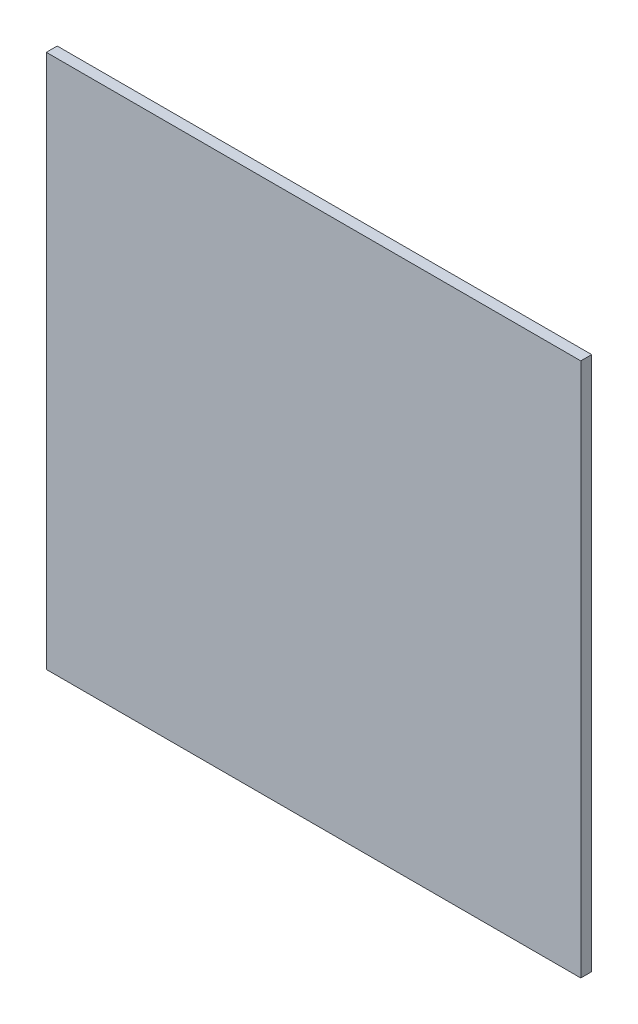
SolidWorks part; units mm, degrees
ref_plane "前视基准面" through (0, 0, 0) normal (0, 0, 1) x (1, 0, 0)
ref_plane "上视基准面" through (0, 0, 0) normal (0, 1, 0) x (1, 0, 0)
ref_plane "右视基准面" through (0, 0, 0) normal (1, 0, 0) x (0, 0, -1)
sketch "草图1" plane through (0, 0, 0) normal (0, 0, 1) x (1, 0, 0)
  line L1 (-2.45, -2.45) -> (2.45, -2.45)
  line L2 (-2.45, -2.45) -> (-2.45, 2.45)
  line L3 (-2.45, 2.45) -> (2.45, 2.45)
  line L4 (2.45, -2.45) -> (2.45, 2.45)
  line L5 (-2.45, -2.45) -> (2.45, 2.45) construction
  line L6 (-2.45, 2.45) -> (2.45, -2.45) construction
  point P0 (0, 0)
  dimension "D1" = 4.9
  dimension "D2" = 4.9
extrude "凸台-拉伸1" add sketch "草图1" along normal blind 0.1
